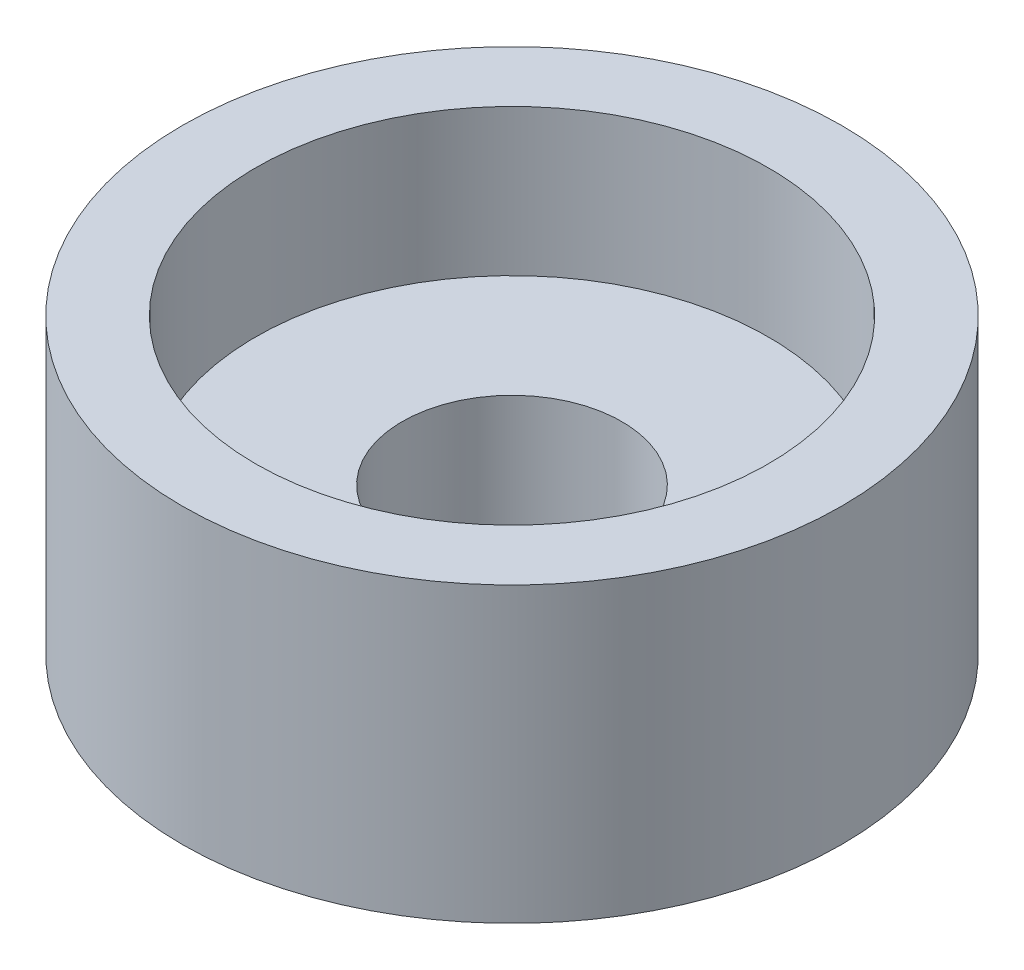
SolidWorks part; units mm, degrees
ref_plane "前视基准面" through (0, 0, 0) normal (0, 0, 1) x (1, 0, 0)
ref_plane "上视基准面" through (0, 0, 0) normal (0, 1, 0) x (1, 0, 0)
ref_plane "右视基准面" through (0, 0, 0) normal (1, 0, 0) x (0, 0, -1)
sketch "草图1" plane through (0, 0, 0) normal (0, 1, 0) x (1, 0, 0)
  circle A0 centre (0, 0) radius 4.5
  dimension "D1" = 9
extrude "凸台-拉伸1" add sketch "草图1" along normal mid plane 4 contours A0
sketch "草图2" plane through (0, 2, 0) normal (0, 1, 0) x (1, 0, 0)
  circle A0 centre (0, 0) radius 3.5
  dimension "D1" = 7
extrude "切除-拉伸1" cut sketch "草图2" against normal blind 2
sketch "草图3" plane through (0, 0, 0) normal (0, 1, 0) x (1, 0, 0)
  circle A0 centre (0, 0) radius 1.5
  dimension "D1" = 3
extrude "切除-拉伸2" cut sketch "草图3" against normal through all
